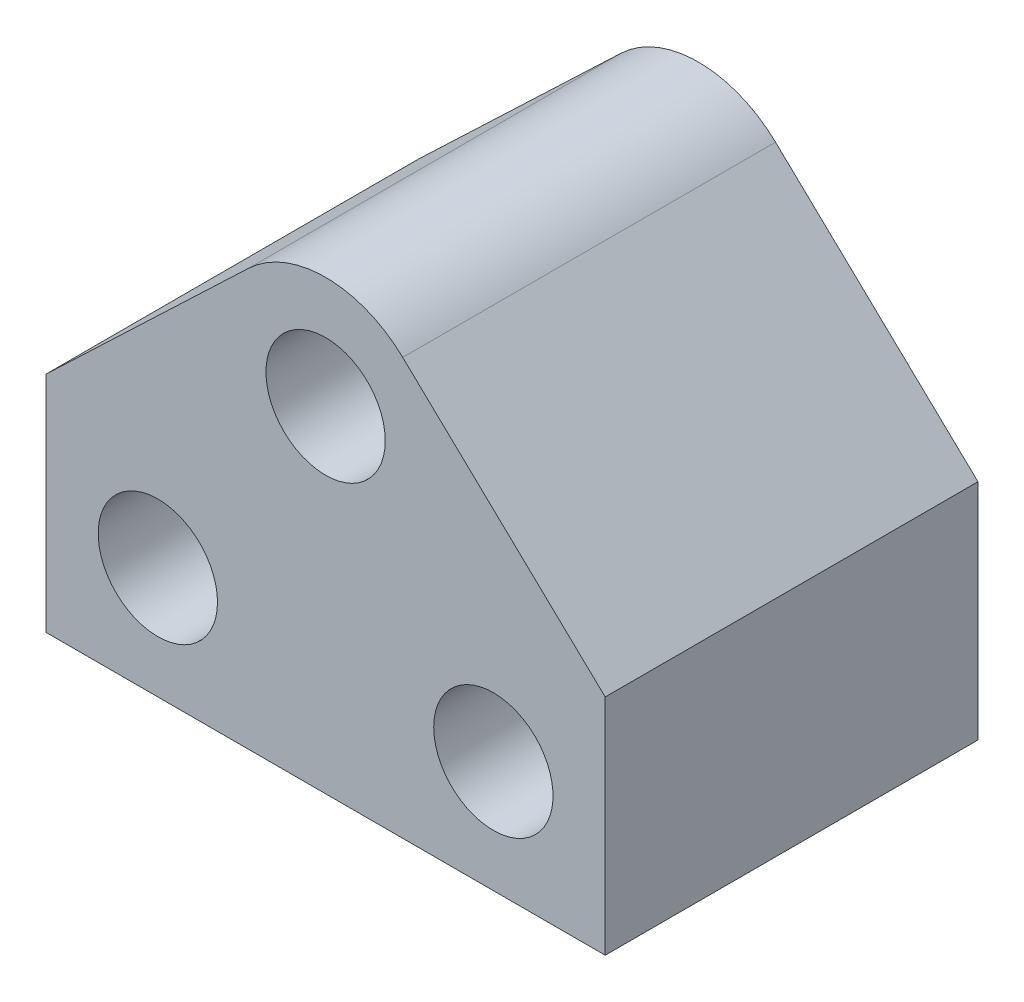
SolidWorks part; units mm, degrees
ref_plane "Front Plane" through (0, 0, 0) normal (0, 0, 1) x (1, 0, 0)
ref_plane "Top Plane" through (0, 0, 0) normal (0, 1, 0) x (1, 0, 0)
ref_plane "Right Plane" through (0, 0, 0) normal (1, 0, 0) x (0, 0, -1)
sketch "Sketch1" plane through (0, 0, 0) normal (0, 0, 1) x (1, 0, 0)
  line L0 (-7.5, 6) -> (-2.069, 11.1724)
  line L1 (2.069, 11.1724) -> (7.5, 6)
  line L2 (7.5, 0) -> (-7.5, 0)
  line L3 (0, 9) -> (0, 0) construction
  line L4 (-7.5, 0) -> (-7.5, 6)
  line L5 (7.5, 0) -> (7.5, 6)
  arc A0 (-2.069, 11.1724) -> (2.069, 11.1724) centre (0, 9) cw
  circle A1 centre (0, 9) radius 1.6
  circle A2 centre (-4.5, 3) radius 1.6
  circle A3 centre (4.5, 3) radius 1.6
  point P13 (0, 0)
  point P16 (-22.3723, 57.2258)
  point P17 (-34.4972, 59.7065)
  point P18 (0, 0)
  dimension "D1" = 3.2
  dimension "D2" = 3
  dimension "D3" = 6
  dimension "D4" = 9
  dimension "D5" = 9
  dimension "D6" = 15
  dimension "D7" = 7.5
extrude "Boss-Extrude1" add sketch "Sketch1" along normal blind 10
